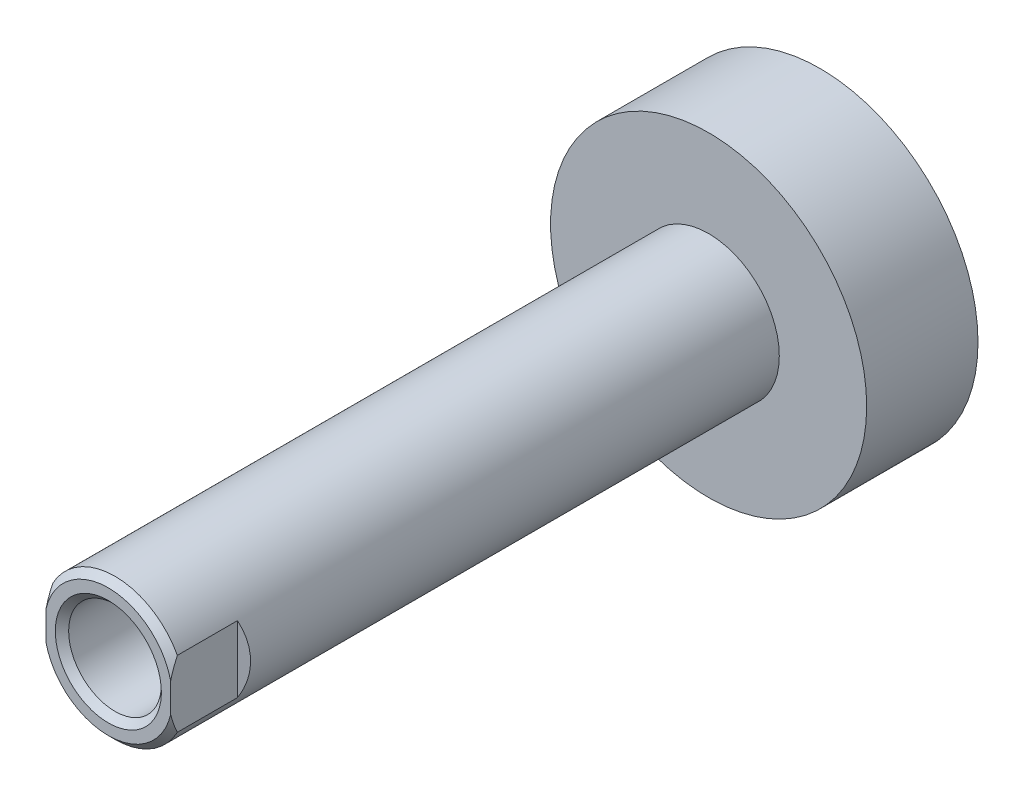
SolidWorks part; units mm, degrees
ref_plane "Front" through (0, 0, 0) normal (0, 0, 1) x (1, 0, 0)
ref_plane "Top" through (0, 0, 0) normal (0, 1, 0) x (1, 0, 0)
ref_plane "Right" through (0, 0, 0) normal (1, 0, 0) x (0, 0, -1)
sketch "Sketch1" plane through (0, 0, 0) normal (0, 0, 1) x (1, 0, 0)
  circle A0 centre (0, 0) radius 7.1
  dimension "D1" = 14.2
extrude "Piston" add sketch "Sketch1" along normal blind 5
sketch "Sketch2" plane through (0, 0, 0) normal (0, 0, -1) x (-1, 0, 0)
  circle A0 centre (0, 0) radius 3.175
  dimension "D1" = 6.35
extrude "Rod" add sketch "Sketch2" against normal up to surface (31.964 mm away)
sketch "Sketch8" plane through (0, 0, 31.964) normal (0, 0, 1) x (1, 0, 0)
  point P0 (0, 0)
hole_wizard "056 #8-32 Internal Thread" positions "3DSketch2" profile "Sketch9" tap size "#8-32" standard "Ansi Inch"
sketch3d "3DSketch2"
  point P0 (0, 0, 31.964)
sketch "Sketch9" plane through (0, 0, 31.964) normal (1, 0, 0) x (0, -1, 0)
  line L0 (0, 0) -> (0, 15.1152)
  line L1 (0, 15.1152) -> (1.7272, 14.0774)
  line L2 (1.7272, 14.0774) -> (1.7272, 11.684)
  line L3 (1.7272, 11.684) -> (2.0828, 11.684)
  line L4 (2.0828, 11.684) -> (2.0828, 0)
  line L5 (2.0828, 0) -> (0, 0)
  line L10 (0, 15.1152) -> (-1.7272, 14.0774) construction
  line L11 (0, -6.35) -> (0, 107.95) construction
  dimension "Tap Drill Dia." = 3.4544
  dimension "Tap Drill Depth" = 14.0774
  dimension "Thread Major Dia." = 4.1656
  dimension "Thread Depth" = 11.684
  dimension "Drill Angle" = 118
hole_wizard "075 #10-32 Internal Thread" [suppressed] positions "3DSketch3" profile "Sketch12" tap size "#10-32" standard "Ansi Inch"
sketch3d "3DSketch3"
  point P0 (0, 0, 50)
sketch "Sketch12" plane through (0, 0, 50) normal (1, 0, 0) x (0, -1, 0)
  line L0 (0, 0) -> (0, 15.2908)
  line L1 (0, 15.2908) -> (2.0193, 14.0774)
  line L2 (2.0193, 14.0774) -> (2.0193, 11.7)
  line L3 (2.0193, 11.7) -> (2.413, 11.7)
  line L4 (2.413, 11.7) -> (2.413, 0)
  line L5 (2.413, 0) -> (0, 0)
  line L10 (0, 15.2908) -> (-2.0193, 14.0774) construction
  line L11 (0, -6.35) -> (0, 107.95) construction
  dimension "Tap Drill Dia." = 4.0386
  dimension "Tap Drill Depth" = 14.0774
  dimension "Thread Major Dia." = 4.826
  dimension "Thread Depth" = 11.684
  dimension "Drill Angle" = 118
hole_wizard "106 5/16-24 Internal Thread" [suppressed] positions "3DSketch4" profile "Sketch13" tap size "5/16-24" standard "Ansi Inch"
sketch3d "3DSketch4"
  point P0 (0, 0, 50)
sketch "Sketch13" plane through (0, 0, 50) normal (1, 0, 0) x (0, -1, 0)
  line L0 (0, 0) -> (0, 18.4532)
  line L1 (0, 18.4532) -> (3.4544, 16.3775)
  line L2 (3.4544, 16.3775) -> (3.4544, 13.2)
  line L3 (3.4544, 13.2) -> (3.9687, 13.2)
  line L4 (3.9687, 13.2) -> (3.9687, 0)
  line L5 (3.9687, 0) -> (0, 0)
  line L10 (0, 18.4532) -> (-3.4544, 16.3775) construction
  line L11 (0, -6.35) -> (0, 107.95) construction
  dimension "Tap Drill Dia." = 6.9088
  dimension "Tap Drill Depth" = 20.4
  dimension "Thread Major Dia." = 7.9375
  dimension "Thread Depth" = 17.78
  dimension "Drill Angle" = 118
hole_wizard "150 3/8-24 Internal Thread" [suppressed] positions "3DSketch5" profile "Sketch14" tap size "3/8-24" standard "Ansi Inch"
sketch3d "3DSketch5"
  point P0 (0, 0, 50)
sketch "Sketch14" plane through (0, 0, 50) normal (1, 0, 0) x (0, -1, 0)
  line L0 (0, 0) -> (0, 18.411)
  line L1 (0, 18.411) -> (4.2164, 15.8775)
  line L2 (4.2164, 15.8775) -> (4.2164, 12.7)
  line L3 (4.2164, 12.7) -> (4.7625, 12.7)
  line L4 (4.7625, 12.7) -> (4.7625, 0)
  line L5 (4.7625, 0) -> (0, 0)
  line L10 (0, 18.411) -> (-4.2164, 15.8775) construction
  line L11 (0, -6.35) -> (0, 107.95) construction
  dimension "Tap Drill Dia." = 8.4328
  dimension "Tap Drill Depth" = 20.4
  dimension "Thread Major Dia." = 9.525
  dimension "Thread Depth" = 17.78
  dimension "Drill Angle" = 118
hole_wizard "200-250 1/2-20 Internal Thread" [suppressed] positions "3DSketch6" profile "Sketch15" tap size "1/2-20" standard "Ansi Inch"
sketch3d "3DSketch6"
  point P0 (0, 0, 122.515)
sketch "Sketch15" plane through (0, 0, 122.515) normal (1, 0, 0) x (0, -1, 0)
  line L0 (0, 0) -> (0, 23.8576)
  line L1 (0, 23.8576) -> (5.7544, 20.4)
  line L2 (5.7544, 20.4) -> (5.7544, 17.78)
  line L3 (5.7544, 17.78) -> (6.35, 17.78)
  line L4 (6.35, 17.78) -> (6.35, 0)
  line L5 (6.35, 0) -> (0, 0)
  line L10 (0, 23.8576) -> (-5.7544, 20.4) construction
  line L11 (0, -6.35) -> (0, 107.95) construction
  dimension "Tap Drill Dia." = 11.5087
  dimension "Tap Drill Depth" = 20.4
  dimension "Thread Major Dia." = 12.7
  dimension "Thread Depth" = 17.78
  dimension "Drill Angle" = 118
chamfer "Rod End Chamfer" distance 0.3 angle 45 2 edges at (0, 3.175, 31.964) (0, -2.0828, 31.964)
sketch "Sketch11" plane through (0, 0, 0) normal (0, 1, 0) x (1, 0, 0)
  line L0 (0, -31.964) -> (0, -54.2319) construction
  line L1 (-2.8, -31.964) -> (-2.8, -28.964)
  line L2 (2.8, -31.964) -> (2.8, -28.964)
  line L3 (-2.8, -28.964) -> (-7.8, -26.0772)
  line L4 (2.8, -28.964) -> (7.8, -26.0772)
  line L5 (-7.8, -26.0772) -> (-7.8, -31.964)
  line L6 (7.8, -26.0772) -> (7.8, -31.964)
  line L7 (-7.8, -31.964) -> (-2.8, -31.964)
  line L8 (7.8, -31.964) -> (2.8, -31.964)
  line L9 (-3.175, -31.964) -> (3.175, -31.964) construction
  dimension "D1" = 60
  dimension "D2" = 5
  dimension "D3" = 3
  dimension "D4" = 5.6
extrude "Wrench Flats" cut sketch "Sketch11" against normal through all and the other way through all
sketch "Sketch16" plane through (0, 0, 31.964) normal (0, 0, 1) x (1, 0, 0)
  circle A0 centre (0, 0) radius 2.0828
  dimension "D1" = 4.1656
extrude "External Thread" [suppressed] add sketch "Sketch16" along normal blind 9.652
chamfer "External Rod Thread Chamfer" [suppressed] distance 0.3 angle 45
hole_wizard "300 5/8-18 Internal Thread" [suppressed] positions "3DSketch7" profile "Sketch17" tap size "5/8-18" standard "Ansi Inch"
sketch3d "3DSketch7"
  arc A0 (7.95, 3.0778, 122.515) -> (-7.95, 3.0778, 122.515) centre (0, 0, 122.515) ccw construction
  point P6 (0, 0, 122.515)
  point P15 (0, 0, 131.04)
sketch "Sketch17" plane through (0, 0, 122.515) normal (1, 0, 0) x (0, -1, 0)
  line L0 (0, 0) -> (0, 19.8164)
  line L1 (0, 19.8164) -> (7.3419, 15.405)
  line L2 (7.3419, 15.405) -> (7.3419, 11.176)
  line L3 (7.3419, 11.176) -> (7.9375, 11.176)
  line L4 (7.9375, 11.176) -> (7.9375, 0)
  line L5 (7.9375, 0) -> (0, 0)
  line L10 (0, 19.8164) -> (-7.3419, 15.405) construction
  line L11 (0, -6.35) -> (0, 107.95) construction
  dimension "Tap Drill Dia." = 14.6837
  dimension "Tap Drill Depth" = 15.405
  dimension "Thread Major Dia." = 15.875
  dimension "Thread Depth" = 11.176
  dimension "Drill Angle" = 118
hole_wizard "400 3/4-16 Internal Thread" [suppressed] positions "3DSketch8" profile "Sketch18" tap size "3/4-16" standard "Ansi Inch"
sketch3d "3DSketch8"
  arc A0 (11.176, 3.4622, 122.515) -> (-11.176, 3.4622, 122.515) centre (0, 0, 122.515) ccw construction
  point P0 (0, 0, 122.515)
  point P9 (0, 0, 134.215)
sketch "Sketch18" plane through (0, 0, 122.515) normal (1, 0, 0) x (0, -1, 0)
  line L0 (0, 0) -> (0, 21.7563)
  line L1 (0, 21.7563) -> (8.7312, 16.51)
  line L2 (8.7312, 16.51) -> (8.7312, 16.448)
  line L3 (8.7312, 16.448) -> (9.525, 16.448)
  line L4 (9.525, 16.448) -> (9.525, 0)
  line L5 (9.525, 0) -> (0, 0)
  line L10 (0, 21.7563) -> (-8.7313, 16.51) construction
  line L11 (0, -6.35) -> (0, 107.95) construction
  dimension "Tap Drill Dia." = 17.4625
  dimension "Tap Drill Depth" = 16.51
  dimension "Thread Major Dia." = 19.05
  dimension "Thread Depth" = 16.448
  dimension "Drill Angle" = 118
